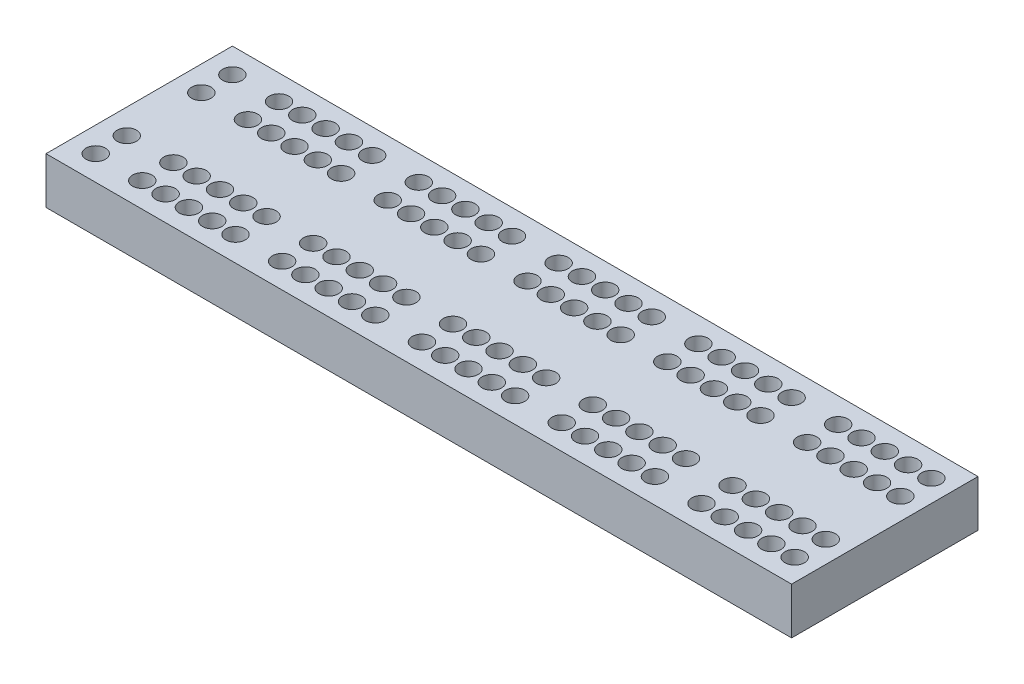
SolidWorks part; units mm, degrees
ref_plane "Front Plane" through (0, 0, 0) normal (0, 0, 1) x (1, 0, 0)
ref_plane "Top Plane" through (0, 0, 0) normal (0, 1, 0) x (1, 0, 0)
ref_plane "Right Plane" through (0, 0, 0) normal (1, 0, 0) x (0, 0, -1)
sketch "Sketch1" plane through (0, 0, 0) normal (0, 0, 1) x (1, 0, 0)
  line L1 (0, 0) -> (304.8, 0)
  line L2 (0, 0) -> (0, -19.05)
  line L3 (0, -19.05) -> (304.8, -19.05)
  line L4 (304.8, 0) -> (304.8, -19.05)
  dimension "D1" = 19.05
  dimension "D2" = 304.8
extrude "Boss-Extrude1" add sketch "Sketch1" along normal mid plane 76.2
hole_wizard "5/16 (0.3125) Diameter Hole1" positions "Sketch3" profile "Sketch4" hole size "5/16" standard "ANSI Inch"
sketch "Sketch3" plane through (0, 0, 0) normal (0, 1, 0) x (1, 0, 0)
  line L0 (0, -38.1) -> (0, 38.1) construction
  line L1 (304.8, 38.1) -> (0, 38.1) construction
  point P1 (10.16, 27.94)
  dimension "D1" = 10.16
  dimension "D2" = 10.16
sketch "Sketch4" plane through (10.16, 0, -27.94) normal (1, 0, 0) x (0, 0, 1)
  line L0 (0, 0) -> (0, 15.0847)
  line L1 (0, 15.0847) -> (3.9687, 12.7)
  line L2 (3.9687, 12.7) -> (3.9687, 0)
  line L5 (3.9687, 0) -> (0, 0)
  line L10 (0, 15.0847) -> (-3.9688, 12.7) construction
  line L11 (0, -6.35) -> (0, 107.95) construction
  dimension "Hole Dia." = 7.9375
  dimension "Hole Depth" = 12.7
  dimension "Drill Angle" = 118
pattern_linear "LPattern1" count 31 spacing 9.525 along (1, 0, 0) count 2 spacing 12.7 along (0, 0, 1) skipping (1, 0), (1, 1), (7, 0), (7, 1), (13, 0), (13, 1), (19, 0), (19, 1), (25, 0), (25, 1) of "5/16 (0.3125) Diameter Hole1"
mirror "Mirror1" about plane through (0, 0, 0) normal (0, 0, 1) of "LPattern1", "5/16 (0.3125) Diameter Hole1"
